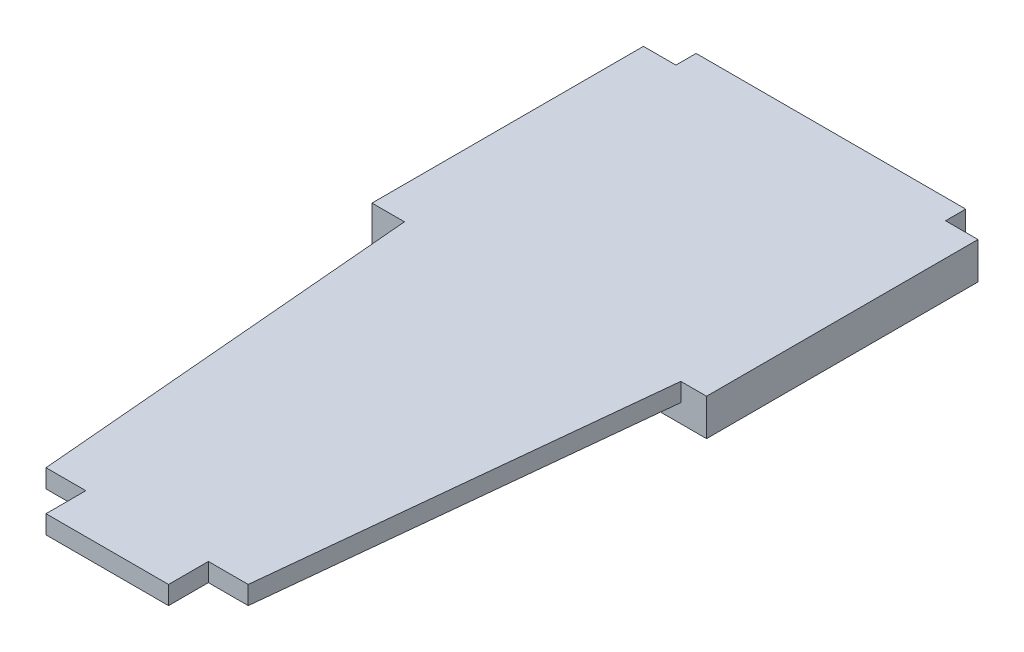
SolidWorks part; units mm, degrees
ref_plane "Front Plane" through (0, 0, 0) normal (0, 0, 1) x (1, 0, 0)
ref_plane "Top Plane" through (0, 0, 0) normal (0, 1, 0) x (1, 0, 0)
ref_plane "Right Plane" through (0, 0, 0) normal (1, 0, 0) x (0, 0, -1)
sketch "Sketch1" plane through (0, 0, 0) normal (0, 1, 0) x (1, 0, 0)
  line L0 (-16.5, 0) -> (-10, 0)
  line L1 (0, 0) -> (0, 64) construction
  line L3 (0, 64) -> (0, 86.8) construction
  line L4 (-27.3, 86.8) -> (27.3, 86.8)
  line L5 (16.5, 0) -> (23.1, 64)
  line L6 (-16.5, 0) -> (-22, 64)
  line L7 (-27.3, 64) -> (27.3, 64)
  line L8 (-27.3, 64) -> (-27.3, 86.8)
  line L9 (27.3, 64) -> (27.3, 86.8)
  line L10 (0, 89.8) -> (0, 108.3)
  line L17 (-27.3, 86.8) -> (-27.3, 108.3)
  line L18 (-10, 0) -> (-10, -6.5)
  line L19 (-10, -6.5) -> (10, -6.5)
  line L20 (-27.3, 108.3) -> (27.3, 108.3)
  line L21 (27.3, 86.8) -> (27.3, 108.3)
  line L24 (0, 108.3) -> (0, 111.6)
  line L25 (-22, 111.6) -> (22, 111.6)
  line L26 (-22, 111.6) -> (-22, 108.3)
  line L27 (22, 111.6) -> (22, 108.3)
  line L28 (10, -6.5) -> (10, 0)
  line L30 (10, 0) -> (16.5, 0)
  point P4 (0, 0)
  point P10 (0, 64)
  point P14 (0, 86.8)
  point P17 (0, 64)
  point P23 (0, 0)
  point P24 (0, 108.3)
  point P32 (0, 111.6)
  dimension "D12" = 64
  dimension "D17" = 6.5
  dimension "D7" = 21.5
  dimension "D1" = 33
  dimension "D2" = 45.1
  dimension "D3" = 54.6
  dimension "D4" = 64
  dimension "D5" = 44.3
  dimension "D6" = 54.6
  dimension "D8" = 18.5
  dimension "D9" = 3.3
  dimension "D10" = 20
  dimension "D11" = 10
  dimension "D13" = 5.3
  dimension "D14" = 0
  dimension "D15" = 44
  dimension "D16" = 23.1
extrude "Boss-Extrude1" add sketch "Sketch1" along normal blind 3
sketch "Sketch2" plane through (0, 0, 0) normal (0, -1, 0) x (1, 0, 0)
  line L0 (22.15, -100.6) -> (22.15, -120.6675) construction
  line L1 (31.9243, -100.6) -> (8.1509, -100.6) construction
  line L2 (-22, -111.6) -> (22, -111.6) construction
  line L3 (27.3, -64) -> (27.3, -108.3) construction
  line L4 (-21.95, -93.5652) -> (-21.95, -114.2218) construction
  line L5 (-30.5006, -100.6) -> (-7.7551, -100.6) construction
  line L6 (-27.3, -64) -> (-27.3, -108.3) construction
  circle A0 centre (23.65, -102.1) radius 1.5
  circle A1 centre (-20.45, -102.1) radius 1.5
  dimension "D3" = 3
  dimension "D6" = 3
  dimension "D1" = 11
  dimension "D2" = 5.15
  dimension "D4" = 5.35
  dimension "D5" = 11
sketch "Sketch3" plane through (0, 0, 0) normal (0, -1, 0) x (1, 0, 0)
  line L0 (-27.3, -108.3) -> (-22, -108.3) construction
  line L1 (-27.3, -64) -> (-27.3, -108.3) construction
  line L2 (-27.3, -64) -> (-22, -64) construction
  line L3 (23.1, -64) -> (27.3, -64) construction
  line L4 (27.3, -64) -> (27.3, -108.3) construction
  line L5 (22, -108.3) -> (27.3, -108.3) construction
  line L6 (22, -111.6) -> (22, -108.3) construction
  line L7 (-22, -111.6) -> (22, -111.6) construction
  line L8 (-27.3, -108.3) -> (-22, -108.3)
  line L9 (-27.3, -64) -> (-27.3, -108.3)
  line L10 (-27.3, -64) -> (-22, -64)
  line L11 (23.1, -64) -> (27.3, -64)
  line L12 (27.3, -64) -> (27.3, -108.3)
  line L13 (22, -108.3) -> (27.3, -108.3)
  line L14 (22, -111.6) -> (22, -108.3)
  line L15 (-22, -111.6) -> (22, -111.6)
  line L16 (-22, -64) -> (23.1, -64)
  point P16 (0, 0)
extrude "Boss-Extrude2" add sketch "Sketch3" along normal blind 3
